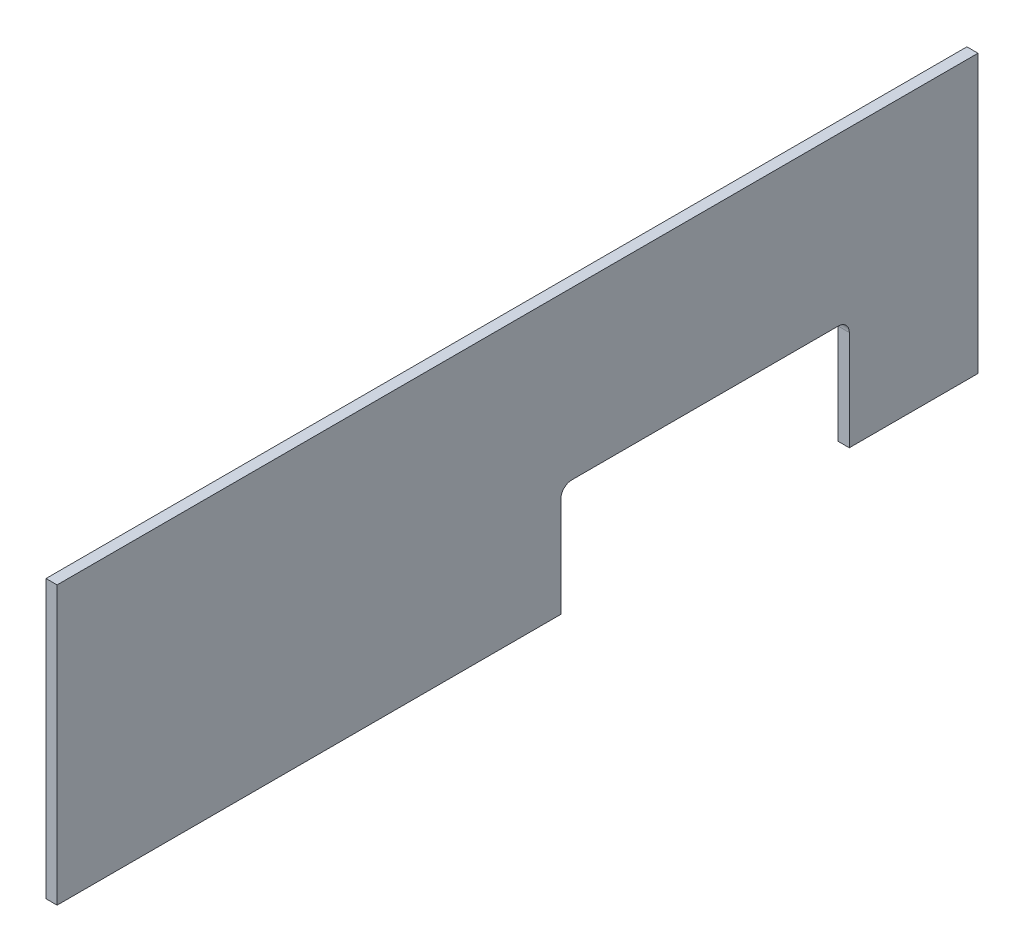
SolidWorks part; units mm, degrees
ref_plane "Front Plane" through (0, 0, 0) normal (0, 0, 1) x (1, 0, 0)
ref_plane "Top Plane" through (0, 0, 0) normal (0, 1, 0) x (1, 0, 0)
ref_plane "Right Plane" through (0, 0, 0) normal (1, 0, 0) x (0, 0, -1)
sketch "Sketch1" plane through (0, 0, 0) normal (1, 0, 0) x (0, 0, -1)
  line L1 (-41.5, -12.5) -> (41.5, -12.5)
  line L2 (-41.5, -12.5) -> (-41.5, 12.5)
  line L3 (-41.5, 12.5) -> (41.5, 12.5)
  line L4 (41.5, -12.5) -> (41.5, 12.5)
  line L5 (-41.5, -12.5) -> (41.5, 12.5) construction
  line L6 (-41.5, 12.5) -> (41.5, -12.5) construction
  line L7 (3.9, -12.5) -> (29.9, -12.5)
  line L8 (3.9, -12.5) -> (3.9, -2.5)
  line L9 (3.9, -2.5) -> (29.9, -2.5)
  line L10 (29.9, -12.5) -> (29.9, -2.5)
  point P0 (0, 0)
  dimension "D1" = 25
  dimension "D2" = 83
  dimension "D3" = 26
  dimension "D4" = 10
  dimension "D5" = 11.6
extrude "Boss-Extrude1" add sketch "Sketch1" along normal blind 1 contours L10 L1 L4 L3 L2 L8 L9
fillet "Fillet1" radius 1 2 edges at (0.5, -2.5, -29.9) (0.5, -2.5, -3.9)
